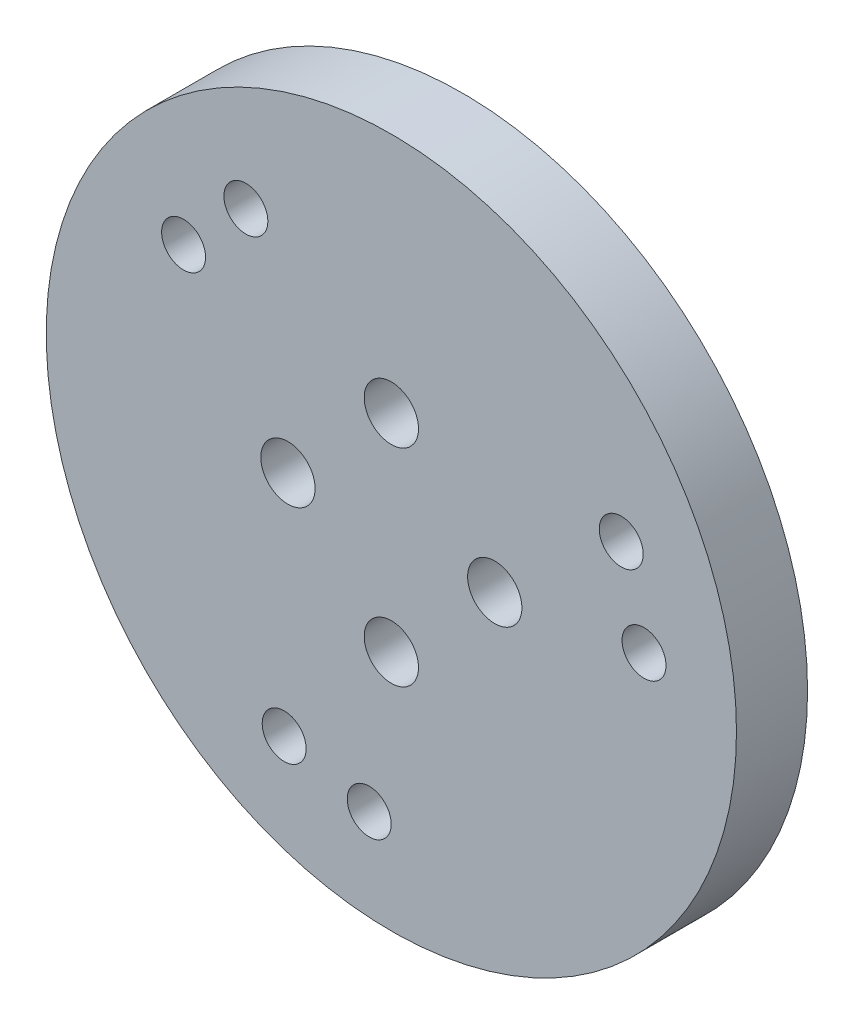
SolidWorks part; units mm, degrees
ref_plane "정면" through (0, 0, 0) normal (0, 0, 1) x (1, 0, 0)
ref_plane "윗면" through (0, 0, 0) normal (0, 1, 0) x (1, 0, 0)
ref_plane "우측면" through (0, 0, 0) normal (1, 0, 0) x (0, 0, -1)
sketch "스케치1" plane through (0, 0, 0) normal (0, 0, 1) x (1, 0, 0)
  line L0 (0, 0) -> (0, 15) construction
  line L1 (0, 0) -> (6.7175, 6.7175) construction
  line L2 (0, 0) -> (-3.2352, 12.0741) construction
  line L4 (0, 0) -> (-10.6066, 10.6066) construction
  circle A0 centre (0, 0) radius 2.3
  circle A1 centre (0, 0) radius 8 construction
  circle A2 centre (0, 0) radius 15
  circle A3 centre (0, 8) radius 1.1
  circle A4 centre (8, 0) radius 1.1
  circle A5 centre (0, -8) radius 1.1
  circle A6 centre (-8, 0) radius 1.1
  circle A7 centre (0, 0) radius 9.5 construction
  circle A9 centre (0, 0) radius 15 construction
  point P17 (0, 0)
  point P25 (0, 0)
  point P28 (0, 0)
  dimension "D1" = 4.6
  dimension "D2" = 16
  dimension "D3" = 30
  dimension "D4" = 2.2
  dimension "D6" = 19
  dimension "D7" = 45
  dimension "D10" = 60
  dimension "D5" = 4
extrude "보스-돌출1" add sketch "스케치1" along normal blind 7
sketch "스케치2" plane through (0, 0, 7) normal (0, 0, 1) x (1, 0, 0)
  circle A0 centre (0, 8) radius 2.1
  circle A1 centre (8, 0) radius 2.1
  circle A2 centre (0, -8) radius 2.1
  circle A3 centre (-8, 0) radius 2.1
  point P12 (0, 0)
  dimension "D2" = 4.2
  dimension "D1" = 4
extrude "컷-돌출1" cut sketch "스케치2" against normal blind 2 and the other way blind 10
sketch "스케치10" plane through (0, 0, 0) normal (0, 0, -1) x (-1, 0, 0)
  circle A0 centre (0, 0) radius 10
  dimension "D1" = 20
extrude "컷-돌출7" cut sketch "스케치10" against normal blind 1.6
sketch "스케치9" plane through (0, 0, 1.6) normal (0, 0, -1) x (-1, 0, 0)
  circle A0 centre (0, 0) radius 4.2
  dimension "D1" = 8.4
extrude "컷-돌출5" cut sketch "스케치9" against normal through all
sketch "스케치11" plane through (0, 0, 7) normal (0, 0, 1) x (1, 0, 0)
  line L0 (0, 0) -> (0, 9.1) construction
  line L1 (0, 0) -> (-9.1, 0) construction
  line L2 (0, 0) -> (-13.8748, 13.8748) construction
  line L3 (0, 0) -> (-11.2547, 16.0734) construction
  line L4 (0, 0) -> (-16.0734, 11.2547) construction
  circle A0 centre (0, 0) radius 26.7
  circle A1 centre (0, 8) radius 1.1 construction
  circle A2 centre (-8, 0) radius 1.1 construction
  circle A3 centre (-11.2547, 16.0734) radius 1.7
  circle A4 centre (-16.0734, 11.2547) radius 1.7
  circle A5 centre (19.5473, 1.7102) radius 1.7
  circle A6 centre (17.7836, 8.2926) radius 1.7
  circle A7 centre (-8.2926, -17.7836) radius 1.7
  circle A8 centre (-1.7102, -19.5473) radius 1.7
  point P24 (0, 0)
  dimension "D1" = 45
  dimension "D2" = 10
  dimension "D3" = 10
extrude "보스-돌출2" add sketch "스케치11" along normal blind 5.5
sketch "스케치13" plane through (0, 0, 7) normal (0, 0, -1) x (-1, 0, 0)
  circle A0 centre (-17.7836, 8.2926) radius 3
  circle A1 centre (-19.5473, 1.7102) radius 3
  circle A2 centre (11.2547, 16.0734) radius 3
  circle A3 centre (16.0734, 11.2547) radius 3
  circle A4 centre (1.7102, -19.5473) radius 3
  circle A5 centre (8.2926, -17.7836) radius 3
extrude "컷-돌출9" cut sketch "스케치13" against normal blind 2.5
sketch "스케치14" plane through (0, 0, 7) normal (0, 0, -1) x (-1, 0, 0)
  circle A0 centre (8, 0) radius 2.1
  circle A1 centre (0, -8) radius 2.1
  circle A2 centre (-8, 0) radius 2.1
  circle A3 centre (0, 8) radius 2.1
extrude "컷-돌출10" cut sketch "스케치14" against normal blind 8
